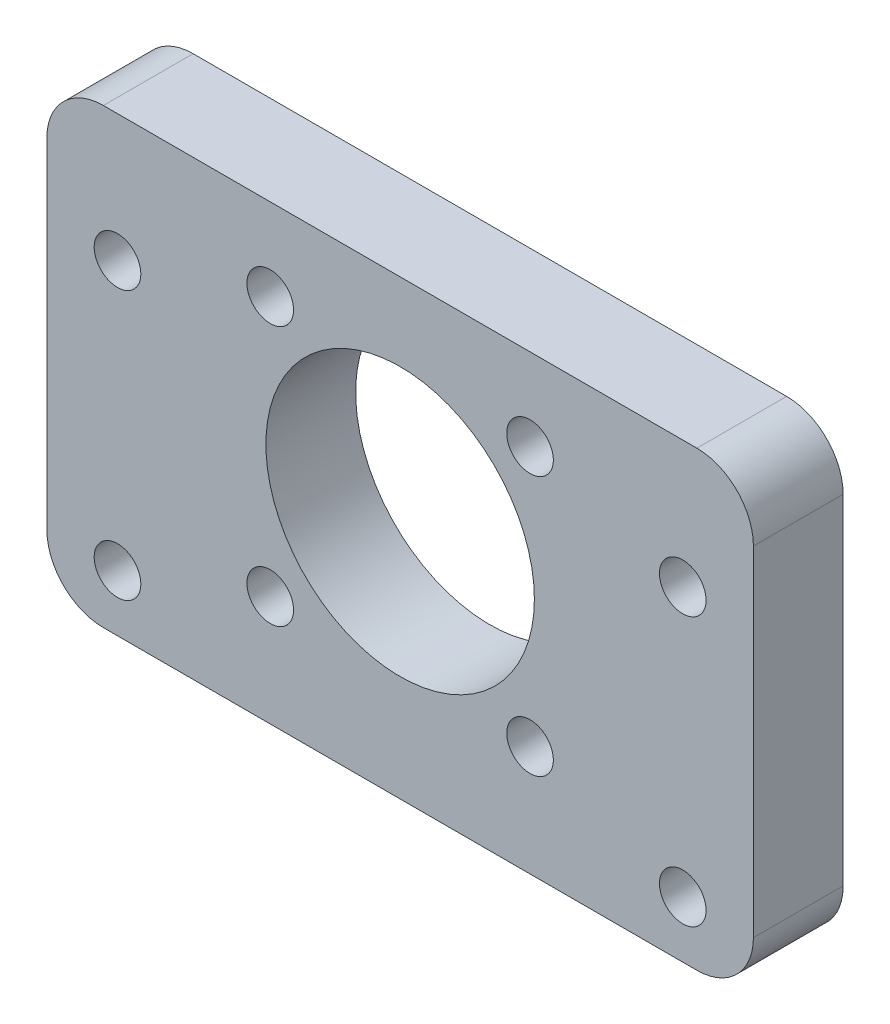
SolidWorks part; units mm, degrees
material "Acrylic (Medium-high impact)"
ref_plane "Front Plane" through (0, 0, 0) normal (0, 0, 1) x (1, 0, 0)
ref_plane "Top Plane" through (0, 0, 0) normal (0, 1, 0) x (1, 0, 0)
ref_plane "Right Plane" through (0, 0, 0) normal (1, 0, 0) x (0, 0, -1)
sketch "Sketch1" plane through (0, 0, 0) normal (0, 0, 1) x (1, 0, 0)
  line L0 (0, 0) -> (-12.0293, 12.0293) construction
  line L1 (-25, 15) -> (25, 15)
  line L2 (-25, 15) -> (-25, -17)
  line L3 (-25, -17) -> (25, -17)
  line L4 (25, 15) -> (25, -17)
  line L5 (-9.1924, 9.1924) -> (9.1924, 9.1924) construction
  line L6 (0, 0) -> (0, -17) construction
  circle A0 centre (0, 0) radius 9.5
  circle A1 centre (-9.1924, 9.1924) radius 1.65
  circle A2 centre (9.1924, 9.1924) radius 1.65
  circle A3 centre (9.1924, -9.1924) radius 1.65
  circle A4 centre (-9.1924, -9.1924) radius 1.65
  point P19 (0, 0)
  dimension "D1" = 19
  dimension "D2" = 13
  dimension "D3" = 3.3
  dimension "D5" = 15
  dimension "D6" = 17
  dimension "D7" = 50
  dimension "D4" = 4
extrude "Boss-Extrude1" add sketch "Sketch1" along normal blind 6.35
sketch "Sketch2" plane through (0, 0, 6.35) normal (0, 0, 1) x (1, 0, 0)
  line L0 (-20, 6) -> (-20, -13) construction
  line L3 (0, 0) -> (0, -13) construction
  line L8 (-20, -13) -> (20, -13) construction
  line L10 (20, -13) -> (20, 6) construction
  circle A0 centre (-20, 6) radius 1.65
  circle A1 centre (-20, -13) radius 1.65
  circle A2 centre (20, -13) radius 1.65
  circle A3 centre (20, 6) radius 1.65
  dimension "D3" = 3.3
  dimension "D1" = 20
  dimension "D2" = 19
  dimension "D4" = 13
extrude "Cut-Extrude1" cut sketch "Sketch2" against normal through all
fillet "Fillet1" radius 4 4 edges at (25, -17, 3.175) (-25, -17, 3.175) (25, 15, 3.175) (-25, 15, 3.175)
